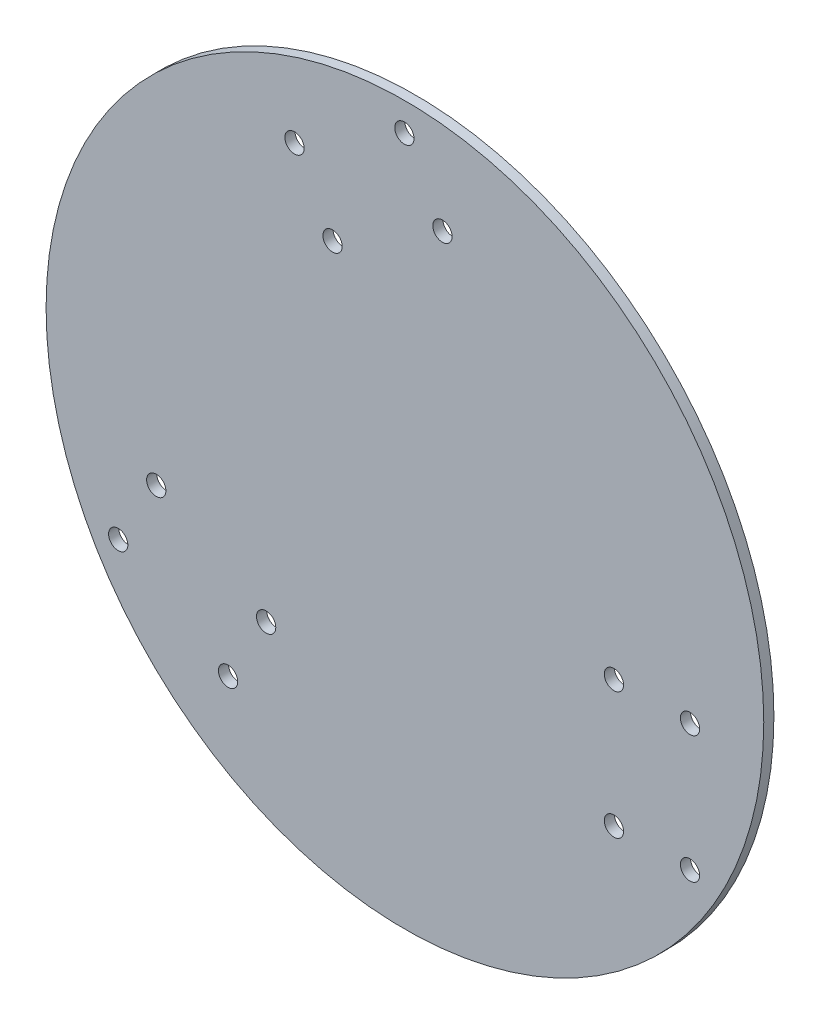
SolidWorks part; units mm, degrees
ref_plane "正面" through (0, 0, 0) normal (0, 0, 1) x (1, 0, 0)
ref_plane "平面" through (0, 0, 0) normal (0, 1, 0) x (1, 0, 0)
ref_plane "右側面" through (0, 0, 0) normal (1, 0, 0) x (0, 0, -1)
sketch "ｽｹｯﾁ1" plane through (0, 0, 0) normal (0, 0, 1) x (1, 0, 0)
  line L1 (50, -50) -> (-50, -50) construction
  line L2 (50, -50) -> (50, 50) construction
  line L3 (50, 50) -> (-50, 50) construction
  line L4 (-50, -50) -> (-50, 50) construction
  line L5 (50, -50) -> (-50, 50) construction
  line L6 (50, 50) -> (-50, -50) construction
  circle A0 centre (0, 0) radius 70.7107
  point P0 (0, 0)
  dimension "D1" = 100
  dimension "D2" = 100
extrude "ﾎﾞｽ - 押し出し1" add sketch "ｽｹｯﾁ1" along normal blind 2 contours A0
sketch "ｽｹｯﾁ2" plane through (0, 0, 0) normal (0, 0, 1) x (1, 0, 0)
  line L1 (56.18, -32.5) -> (41.18, -32.5) construction
  line L2 (56.18, -32.5) -> (56.18, -7.5) construction
  line L3 (56.18, -7.5) -> (41.18, -7.5) construction
  line L4 (41.18, -32.5) -> (41.18, -7.5) construction
  line L5 (56.18, -32.5) -> (41.18, -7.5) construction
  line L6 (56.18, -7.5) -> (41.18, -32.5) construction
  circle A0 centre (41.18, -7.5) radius 1.9
  circle A1 centre (41.18, -32.5) radius 1.9
  circle A2 centre (56.18, -32.5) radius 1.9
  circle A3 centre (56.18, -7.5) radius 1.9
  point P0 (48.68, -20)
  dimension "D3" = 3.8
  dimension "D1" = 15
  dimension "D2" = 25
  dimension "D4" = 48.68
  dimension "D5" = 20
extrude "ｶｯﾄ - 押し出し2" cut sketch "ｽｹｯﾁ2" against normal through all both and the other way through all
pattern_circular "円形ﾊﾟﾀｰﾝ1" count 3 over 360 about axis through (-0.141, 0.0579, 0) along (0, 0, 1) of "ｶｯﾄ - 押し出し2"
equation "\"D4@ｽｹｯﾁ2\"=20.000mm+28.68"
